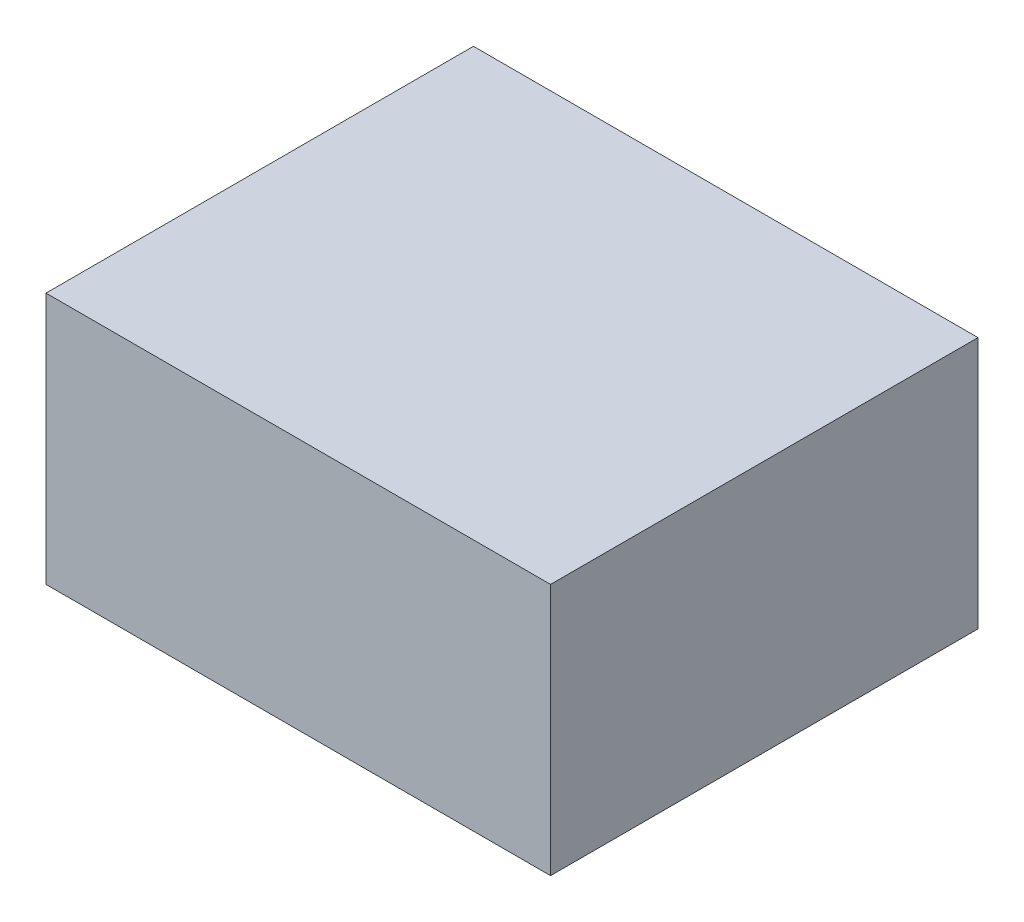
SolidWorks part; units mm, degrees
ref_plane "Front Plane" through (0, 0, 0) normal (0, 0, 1) x (1, 0, 0)
ref_plane "Top Plane" through (0, 0, 0) normal (0, 1, 0) x (1, 0, 0)
ref_plane "Right Plane" through (0, 0, 0) normal (1, 0, 0) x (0, 0, -1)
sketch "Sketch1" plane through (0, 0, 0) normal (0, 0, 1) x (1, 0, 0)
  line L1 (0, 0) -> (14.9905, 0)
  line L2 (0, 0) -> (0, 7.4953)
  line L3 (0, 7.4953) -> (14.9905, 7.4953)
  line L4 (14.9905, 0) -> (14.9905, 7.4953)
extrude "Boss-Extrude1" add sketch "Sketch1" along normal blind 12.7
